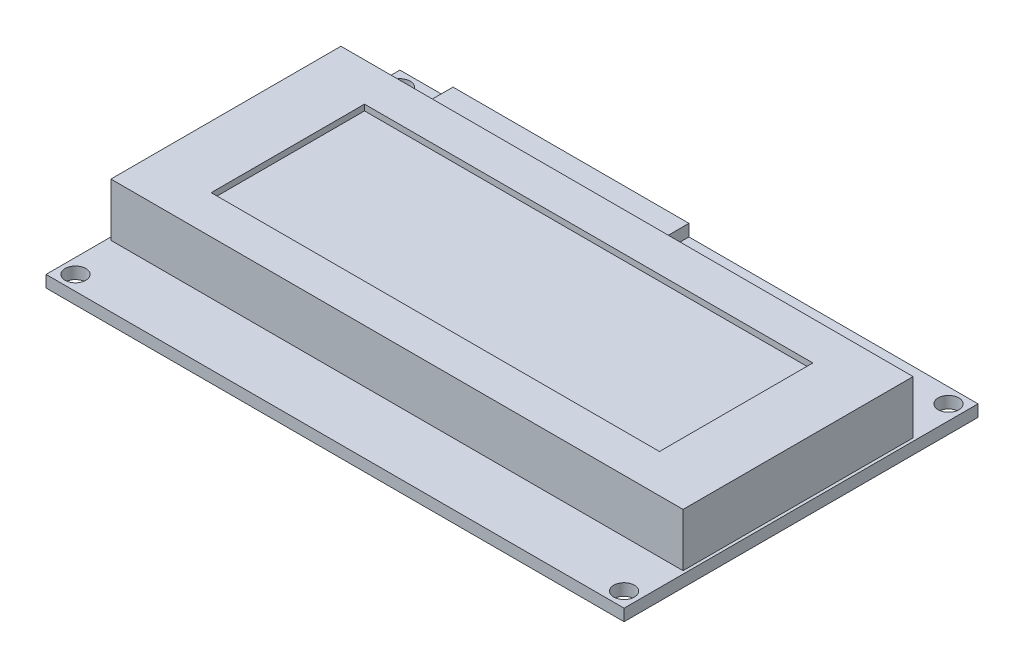
SolidWorks part; units mm, degrees
ref_plane "Front Plane" through (0, 0, 0) normal (0, 0, 1) x (1, 0, 0)
ref_plane "Top Plane" through (0, 0, 0) normal (0, 1, 0) x (1, 0, 0)
ref_plane "Right Plane" through (0, 0, 0) normal (1, 0, 0) x (0, 0, -1)
sketch "Sketch1" plane through (0, 0, 0) normal (0, 1, 0) x (1, 0, 0)
  line L0 (0, 30) -> (0, -30) construction
  line L1 (-49, -30) -> (49, -30)
  line L2 (-49, -30) -> (-49, 30)
  line L3 (-49, 30) -> (49, 30)
  line L4 (49, -30) -> (49, 30)
  dimension "D1" = 98
  dimension "D2" = 60
extrude "Boss-Extrude1" add sketch "Sketch1" along normal blind 2
sketch "Sketch2" plane through (0, 2, 0) normal (0, 1, 0) x (1, 0, 0)
  line L0 (0, 19.5) -> (0, -19.5) construction
  line L1 (-48.5, 19.5) -> (48.5, 19.5)
  line L2 (-48.5, 19.5) -> (-48.5, -19.5)
  line L3 (-48.5, -19.5) -> (48.5, -19.5)
  line L4 (48.5, 19.5) -> (48.5, -19.5)
  line L6 (-49, 30) -> (-49, -30) construction
  dimension "D1" = 0.5
  dimension "D2" = 39
extrude "Boss-Extrude2" add sketch "Sketch2" along normal blind 9 separate body
sketch "Sketch3" plane through (0, 11, 0) normal (0, 1, 0) x (1, 0, 0)
  line L0 (0, 13) -> (0, -13) construction
  line L1 (-38, 13) -> (38, 13)
  line L2 (-38, 13) -> (-38, -13)
  line L3 (-38, -13) -> (38, -13)
  line L4 (38, 13) -> (38, -13)
  dimension "D1" = 76
  dimension "D2" = 26
extrude "Cut-Extrude1" cut sketch "Sketch3" against normal blind 1
sketch "Sketch4" plane through (0, 0, 0) normal (0, -1, 0) x (1, 0, 0)
  line L0 (49, -30) -> (-49, -30) construction
  line L1 (0.5, -28.5) -> (-41, -28.5)
  line L2 (0.5, -28.5) -> (0.5, -9.5)
  line L3 (0.5, -9.5) -> (-41, -9.5)
  line L4 (-41, -28.5) -> (-41, -9.5)
  line L5 (-49, -30) -> (-49, 30) construction
  dimension "D1" = 1.5
  dimension "D2" = 19
  dimension "D3" = 41.5
  dimension "D4" = 8
extrude "Boss-Extrude3" add sketch "Sketch4" along normal blind 8 separate body
sketch "Sketch5" plane through (0, 2, 0) normal (0, 1, 0) x (1, 0, 0)
  line L0 (-49, 30) -> (-49, -30) construction
  line L1 (49, 30) -> (-49, 30) construction
  line L2 (49, -30) -> (49, 30) construction
  line L3 (-49, -30) -> (49, -30) construction
  circle A0 centre (-46.5, 27.5) radius 1.75
  circle A1 centre (46.5, 27.5) radius 1.75
  circle A2 centre (46.5, -27.5) radius 1.75
  circle A3 centre (-46.5, -27.5) radius 1.75
  dimension "D5" = 3.5
  dimension "D1" = 2.5
  dimension "D2" = 2.5
  dimension "D3" = 2.5
  dimension "D4" = 2.5
extrude "Cut-Extrude2" cut sketch "Sketch5" against normal through all
sketch "Sketch6" plane through (0, 2, 0) normal (0, 1, 0) x (1, 0, 0)
  line L0 (49, 30) -> (-49, 30) construction
  line L1 (-40, 30) -> (0, 30)
  line L2 (-40, 30) -> (-40, 26)
  line L3 (-40, 26) -> (0, 26)
  line L4 (0, 30) -> (0, 26)
  line L5 (-49, 30) -> (-49, -30) construction
  dimension "D1" = 9
  dimension "D2" = 40
  dimension "D3" = 4
extrude "Boss-Extrude4" add sketch "Sketch6" along normal blind 2 separate body
